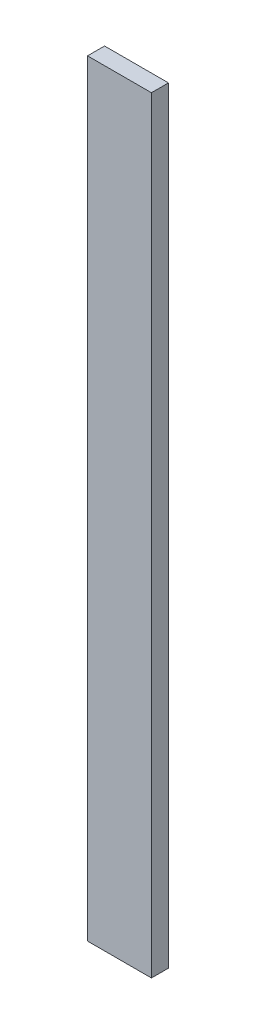
SolidWorks part; units mm, degrees
ref_plane "Front Plane" through (0, 0, 0) normal (0, 0, 1) x (1, 0, 0)
ref_plane "Top Plane" through (0, 0, 0) normal (0, 1, 0) x (1, 0, 0)
ref_plane "Right Plane" through (0, 0, 0) normal (1, 0, 0) x (0, 0, -1)
sketch "Croquis1" plane through (0, 0, 0) normal (0, 0, 1) x (1, 0, 0)
  line L1 (-15, 180) -> (15, 180)
  line L2 (-15, 180) -> (-15, -180)
  line L3 (-15, -180) -> (15, -180)
  line L4 (15, 180) -> (15, -180)
  line L5 (-15, 180) -> (15, -180) construction
  line L6 (-15, -180) -> (15, 180) construction
  point P0 (0, 0)
  dimension "D1" = 360
  dimension "D2" = 30
extrude "Saliente-Extruir1" add sketch "Croquis1" along normal blind 8
